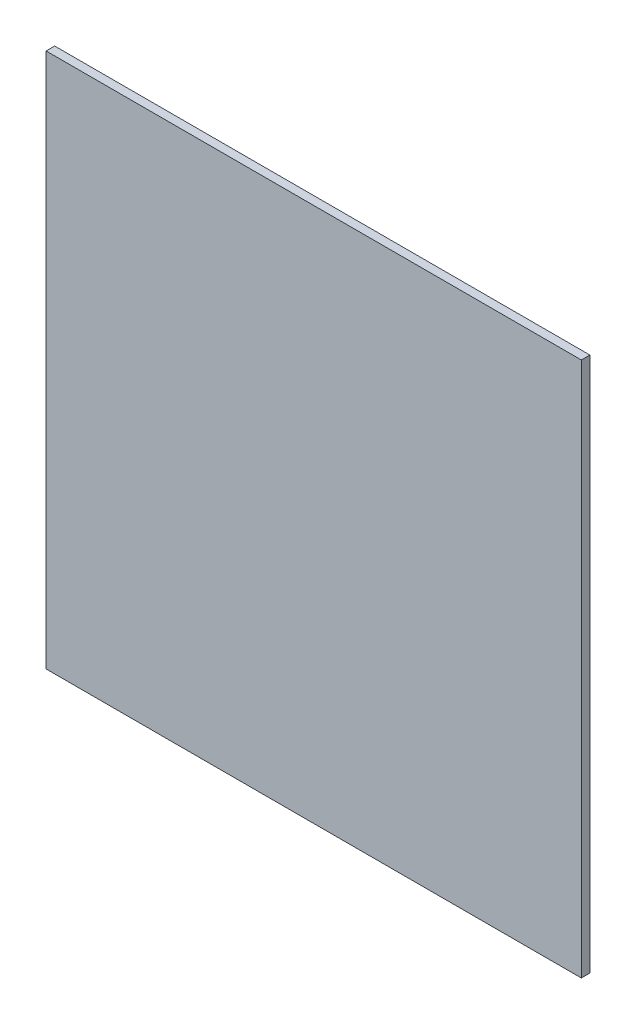
SolidWorks part; units mm, degrees
ref_plane "Спереди" through (0, 0, 0) normal (0, 0, 1) x (1, 0, 0)
ref_plane "Сверху" through (0, 0, 0) normal (0, 1, 0) x (1, 0, 0)
ref_plane "Справа" through (0, 0, 0) normal (1, 0, 0) x (0, 0, -1)
sketch "Эскиз1" plane through (0, 0, 0) normal (0, 0, 1) x (1, 0, 0)
  line L1 (-62.5, -62.5) -> (62.5, -62.5)
  line L2 (-62.5, -62.5) -> (-62.5, 62.5)
  line L3 (-62.5, 62.5) -> (62.5, 62.5)
  line L4 (62.5, -62.5) -> (62.5, 62.5)
  line L5 (-62.5, -62.5) -> (62.5, 62.5) construction
  line L6 (-62.5, 62.5) -> (62.5, -62.5) construction
  point P0 (0, 0)
  dimension "D1" = 125
  dimension "D2" = 125
extrude "Бобышка-Вытянуть1" add sketch "Эскиз1" along normal blind 2
